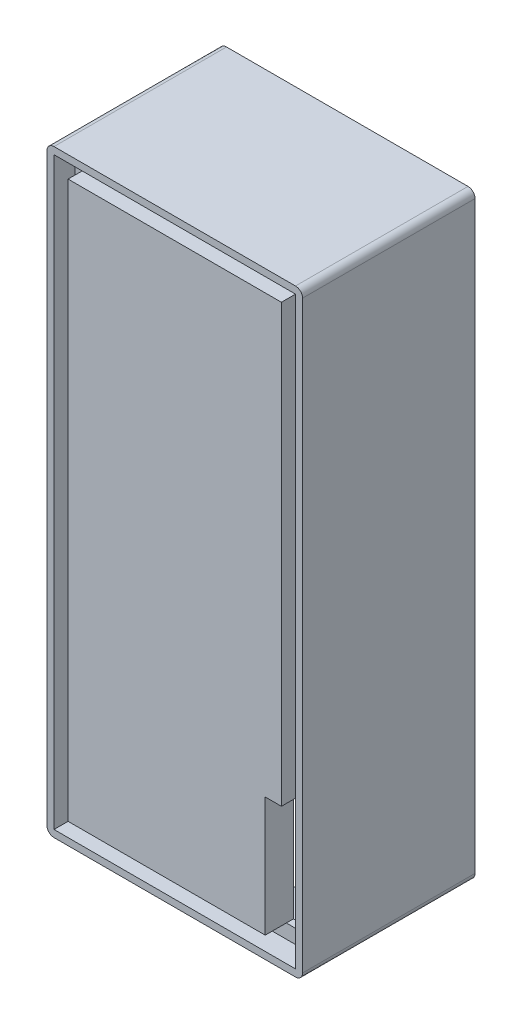
SolidWorks part; units mm, degrees
ref_plane "Ebene vorne" through (0, 0, 0) normal (0, 0, 1) x (1, 0, 0)
ref_plane "Ebene oben" through (0, 0, 0) normal (0, 1, 0) x (1, 0, 0)
ref_plane "Ebene rechts" through (0, 0, 0) normal (1, 0, 0) x (0, 0, -1)
sketch "Skizze1" plane through (0, 0, 0) normal (0, 0, 1) x (1, 0, 0)
  line L1 (-36.3, 85) -> (0, 85)
  line L2 (-36.3, 85) -> (-36.3, 0)
  line L3 (-36.3, 0) -> (0, 0)
  line L4 (0, 85) -> (0, 0)
  dimension "D1" = 36.3
  dimension "D2" = 85
extrude "Aufsatz-Linear austragen1" add sketch "Skizze1" along normal blind 21.5 contours L2 L3 L4 L1
shell "Wandung1" thickness 1
ref_plane "Ebene1" through (-18.15, 0, 0) normal (1, 0, 0) x (0, 0, -1)
extrude "Schnitt-Linear austragen1" cut sketch "Skizze4" against normal blind 10
sketch "Skizze4" plane through (-35.3, 59.7494, -1119.9252) normal (1, 0, 0) x (0, -1, 0)
  line L5 (52.0144, -1139.2202) -> (44.4844, -1139.2202) construction
  line L8 (45.5235, -1137.0131) -> (50.9735, -1137.0131) construction
  line L11 (52.7644, -1139.0202) -> (43.7344, -1139.0202)
  line L12 (52.7644, -1139.0202) -> (52.7644, -1135.9131)
  line L13 (52.7644, -1135.9131) -> (43.7344, -1135.9131)
  line L14 (43.7344, -1139.0202) -> (43.7344, -1135.9131)
sketch "Skizze6" plane through (0, 0, 20.5) normal (0, 0, -1) x (-1, 0, 0)
  line L0 (5.3, 20) -> (3, 20)
  line L5 (3, 20) -> (3, 3)
  line L6 (3, 3) -> (5.3, 3)
  line L8 (5.3, 20) -> (5.3, 3)
  line L9 (35.3, 84) -> (35.3, 1) construction
  line L10 (1, 84) -> (1, 1) construction
  line L11 (35.3, 1) -> (1, 1) construction
  dimension "D1" = 30
  dimension "D2" = 2
  dimension "D3" = 2
sketch "Skizze8" plane through (0, 0, 21.5) normal (0, 0, 1) x (1, 0, 0)
  line L0 (-35.3, 1) -> (-1, 1)
  line L1 (-1, 84) -> (-1, 1)
  line L2 (-35.3, 84) -> (-1, 84)
  line L3 (-35.3, 84) -> (-35.3, 1)
  line L31 (-36.3, 85) -> (-36.3, 0) construction
  line L32 (-36.3, 0) -> (0, 0) construction
  line L34 (0, 85) -> (0, 0) construction
  line L35 (-36.3, 85) -> (0, 85) construction
  line L36 (-36.3, 0) -> (0, 0)
  line L37 (0, 85) -> (0, 0)
  line L38 (-36.3, 85) -> (-36.3, 0)
  line L39 (-36.3, 85) -> (0, 85)
  dimension "D1" = 1
extrude "Aufsatz-Linear austragen5" add sketch "Skizze8" along normal blind 3
fillet "Verrundung1" radius 0.9 4 edges at (-35.8, 16.015, 15.9879) (-35.8, 16.015, 19.095) (-35.8, 6.985, 19.095) (-35.8, 6.985, 15.9879)
fillet "Verrundung2" radius 1 4 edges at (0, 85, 12.25) (-36.3, 85, 12.25) (0, 0, 12.25) (-36.3, 0, 12.25)
sketch "Skizze11" plane through (0, 0, 0) normal (0, 0, -1) x (-1, 0, 0)
  line L0 (35.3, 84) -> (35.3, 1) construction
  line L1 (0.8, 22.9494) -> (35.5, 22.9494)
  line L2 (0.8, 22.9494) -> (0.8, 84)
  line L3 (0.8, 84) -> (35.5, 84)
  line L4 (35.5, 22.9494) -> (35.5, 84)
  line L5 (1, 84) -> (1, 1) construction
  dimension "D1" = 0.2
  dimension "D2" = 0.2
extrude "Schnitt-Linear austragen5" cut sketch "Skizze11" against normal up to surface (20.5 mm away) up to face at (-18.15, 42.5, 20.5)
extrude "Schnitt-Linear austragen6" cut sketch "Skizze6" against normal up to surface (1 mm away) up to face at (-18.15, 42.5, 21.5)
sketch "Skizze12" plane through (0, 0, 21.5) normal (0, 0, 1) x (1, 0, 0)
  line L10 (-3, 20) -> (-5.3, 20) construction
  line L11 (-5.3, 20) -> (-5.3, 3) construction
  line L12 (-3, 20) -> (-5.3, 20)
  line L13 (-5.3, 20) -> (-5.3, 3)
  line L14 (-33.3, 3) -> (-3, 3)
  line L15 (-3, 3) -> (-3, 82)
  line L16 (-33.3, 82) -> (-33.3, 3)
  line L17 (-3, 82) -> (-33.3, 82)
  line L18 (-33.3, 3) -> (-5.3, 3)
  line L19 (-3, 20) -> (-3, 82)
  line L20 (-33.3, 82) -> (-33.3, 3)
  line L21 (-3, 82) -> (-33.3, 82)
  dimension "D1" = 2
extrude "Aufsatz-Linear austragen7" add sketch "Skizze12" along normal up to surface (3 mm away) up to face at (-18.15, 42.5, 24.5)
extrude "Schnitt-Linear austragen7" cut sketch "Skizze13" against normal blind 2
sketch "Skizze13" plane through (-2.8226, 1, -1119.9252) normal (0, 1, 0) x (0, 0, -1)
  arc A2 (-1137.2088, 10.1038) -> (-1135.2315, 10.1038) centre (-1136.2202, 10.2538) ccw construction
  arc A3 (-1135.2315, 10.4038) -> (-1137.2088, 10.4038) centre (-1136.2202, 10.2538) ccw construction
  circle A4 centre (-1136.2202, 10.2538) radius 0.55
extrude "Schnitt-Linear austragen8" cut sketch "Skizze14" against normal blind 3
sketch "Skizze14" plane through (-2.8226, 1, -1119.9252) normal (0, 1, 0) x (0, 0, -1)
  line L4 (-1134.4252, 5.2774) -> (-1121.4252, 5.2774)
  line L5 (-1134.4252, 25.3774) -> (-1134.4252, 5.2774)
  line L6 (-1121.4252, 5.2774) -> (-1121.4252, 25.3774)
  line L7 (-1121.4252, 25.3774) -> (-1134.4252, 25.3774)
equation "\"Breite\"=36.3"
equation "\"D1@Skizze1\"=\"Breite\""
equation "\"Länge\"= 85"
equation "\"D2@Skizze1\"=\"Länge\""
